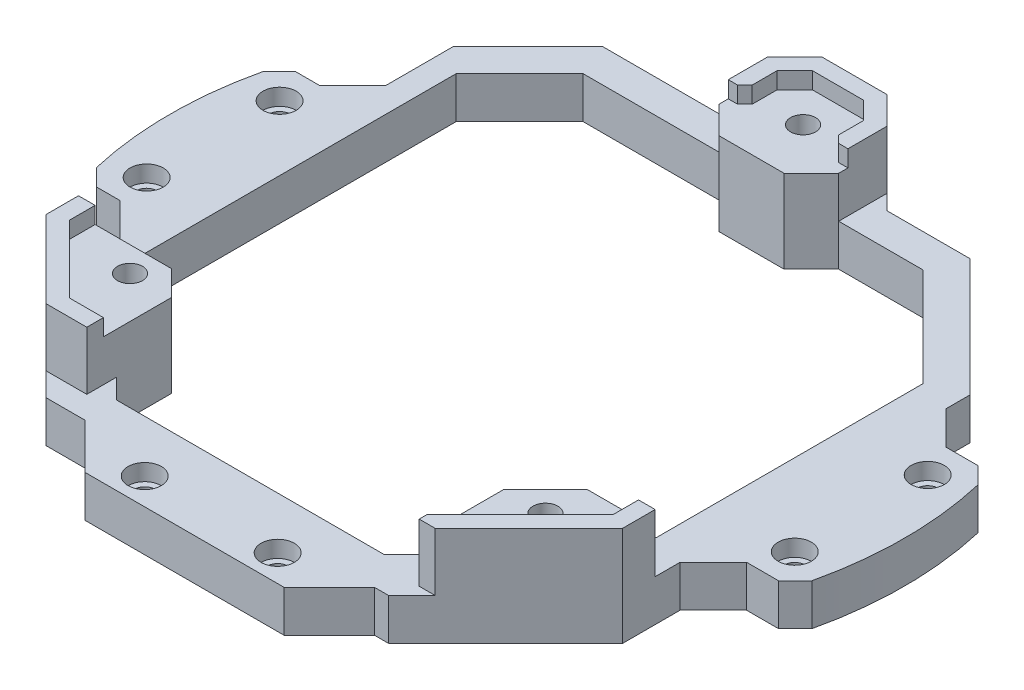
SolidWorks part; units mm, degrees
ref_plane "Спереди" through (0, 0, 0) normal (0, 0, 1) x (1, 0, 0)
ref_plane "Сверху" through (0, 0, 0) normal (0, 1, 0) x (1, 0, 0)
ref_plane "Справа" through (0, 0, 0) normal (1, 0, 0) x (0, 0, -1)
sketch "Эскиз2" plane through (0, 0, 0) normal (0, 1, 0) x (1, 0, 0)
  line L0 (3, 36) -> (-3, 36) construction
  line L1 (3, 36) -> (-3, 36) construction
  line L2 (0, 32) -> (5, 32) construction
  line L3 (5, 31) -> (5, 34) construction
  line L4 (-3.0828, 27.8) -> (-5.2, 29.9172)
  line L5 (5, 34) -> (3, 36) construction
  line L6 (-5, 34) -> (-5, 31) construction
  line L7 (-3, 36) -> (-5, 34) construction
  line L8 (5, 31) -> (5, 34) construction
  line L9 (5, 34) -> (3, 36) construction
  line L10 (-5, 34) -> (-5, 31) construction
  line L11 (-3, 36) -> (-5, 34) construction
  line L12 (5.2, 31) -> (5.2, 34.0828)
  line L13 (5.2, 34.0828) -> (3.0828, 36.2)
  line L14 (3.0828, 36.2) -> (-3.0828, 36.2)
  line L15 (-3.0828, 36.2) -> (-5.2, 34.0828)
  line L16 (-5.2, 34.0828) -> (-5.2, 31)
  line L17 (7.2, 31) -> (7.2, 34.9113)
  line L18 (7.2, 34.9113) -> (3.9113, 38.2)
  line L19 (3.9113, 38.2) -> (-3.9113, 38.2)
  line L20 (-3.9113, 38.2) -> (-7.2, 34.9113)
  line L21 (-7.2, 34.9113) -> (-7.2, 31)
  line L22 (-3.9113, 25.8) -> (-7.2, 29.0887)
  line L23 (5.2, 29.9172) -> (3.0828, 27.8)
  line L24 (3.0828, 27.8) -> (-3.0828, 27.8)
  line L25 (3.9113, 25.8) -> (-3.9113, 25.8)
  line L26 (7.2, 29.0887) -> (3.9113, 25.8)
  line L27 (-5.2, 31) -> (-5.2, 29.9172)
  line L28 (-7.2, 31) -> (-7.2, 29.0887)
  line L29 (5.2, 29.9172) -> (5.2, 31)
  line L30 (7.2, 29.0887) -> (7.2, 31)
  line L33 (20, -33) -> (20, -24)
  line L34 (20, -24) -> (25, -19)
  line L35 (25, -19) -> (31, -19)
  line L36 (31, -22) -> (31, 25) construction
  line L38 (18, -35) -> (31, -22) construction
  line L39 (20, -33) -> (31, -22) construction
  line L40 (21.9113, -34.2) -> (33.2, -22.9113)
  line L41 (20.1414, -33.1414) -> (31.2, -22.0828) construction
  line L43 (31.2, -22.0828) -> (31.2, -19) construction
  line L44 (20.1414, -33.1414) -> (31.1414, -22.1414) construction
  line L45 (33.2, -22.9113) -> (33.2, -19)
  line L46 (20, -33) -> (20.1414, -33.1414)
  line L47 (31, -19) -> (33.2, -19)
  line L48 (-20, -32) -> (-20, -24)
  line L49 (-24, -32) -> (-10, -32) construction
  line L50 (-20, -24) -> (-23, -21)
  line L51 (-23, -21) -> (-32, -21)
  line L52 (-32, 22) -> (-32, -24) construction
  line L53 (-32, -24) -> (-24, -32) construction
  line L54 (-32, -21) -> (-32, -24) construction
  line L55 (-24, -32) -> (-20, -32) construction
  line L56 (-32, -24) -> (-24, -32) construction
  line L57 (-32, 22) -> (-32, -21) construction
  line L58 (-20, -32) -> (-10, -32) construction
  line L59 (-34.2, -21) -> (-34.2, -24.9113)
  line L60 (-34.2, -24.9113) -> (-24.9113, -34.2)
  line L61 (-24.9113, -34.2) -> (-20, -34.2)
  line L62 (-34.2, -21) -> (-32, -21)
  line L63 (-20, -34.2) -> (-20, -32)
  line L64 (-1020, -34.2) -> (48980, -34.2) construction
  line L65 (20, -33) -> (20, -34.2)
  line L66 (20, -34.2) -> (21.9113, -34.2)
  line L68 (21.5556, -34.5556) -> (33.2, -22.9113) construction
  circle A0 centre (25, -24) radius 1.25 construction
  circle A1 centre (0, 32) radius 1.25 construction
  circle A2 centre (-25, -24) radius 1.25 construction
  circle A3 centre (25, -24) radius 1.25 construction
  circle A4 centre (0, 32) radius 1.25 construction
  circle A5 centre (-25, -24) radius 1.25 construction
  circle A6 centre (-25, -24) radius 1.5
  circle A7 centre (25, -24) radius 1.5
  circle A8 centre (0, 32) radius 1.5
  dimension "D1" = 3
  dimension "D4" = 5
  dimension "D5" = 5
  dimension "D7" = 0.2
  dimension "D9" = 5
  dimension "D10" = 3
  dimension "D2" = 0.2
  dimension "D3" = 2
  dimension "D6" = 0.2
  dimension "D8" = 2
  dimension "D11" = 2.2
extrude "Бобышка-Вытянуть2" add sketch "Эскиз2" against normal blind 5 contours L61 L63 L48 L50 L51 L62 L59 L60 A6 | L47 L35 L34 L33 L46 L40 L45 A7 | L26 L30 L17 L18 L19 L20 L21 L28 L22 L25 L29 L23 L24 L4 L27 L16 L15 L14 L13 L12 | L23 L29 L12 L13 L14 L15 L16 L27 L4 L24 A8
sketch "Эскиз3" plane through (0, 0, 0) normal (0, 1, 0) x (1, 0, 0)
  line L11 (-24, -32) -> (-10, -32) construction
  line L12 (7.2, 29.0887) -> (7.2, 34.9113) construction
  line L15 (7.2, 34.9113) -> (3.9113, 38.2) construction
  line L22 (-32, -24) -> (-24, -32) construction
  line L23 (-32, 22) -> (-32, -24) construction
  line L24 (3.9113, 38.2) -> (-3.9113, 38.2) construction
  line L25 (-7.2, 34.9113) -> (-7.2, 29.0887) construction
  line L34 (-3.9113, 38.2) -> (-7.2, 34.9113) construction
  line L35 (7.2, 30.2) -> (7.2, 34.9113)
  line L36 (7.2, 34.9113) -> (3.9113, 38.2)
  line L37 (3.9113, 38.2) -> (-3.9113, 38.2)
  line L38 (-7.2, 34.9113) -> (-7.2, 30.2)
  line L39 (-3.9113, 38.2) -> (-7.2, 34.9113)
  line L40 (26, 30) -> (6, 30) construction
  line L41 (-24, -32) -> (-20, -32) construction
  line L42 (-32, -24) -> (-24, -32) construction
  line L43 (-32, -21) -> (-32, -24) construction
  line L44 (-24.9113, -34.2) -> (-20, -34.2)
  line L45 (-20, -34.2) -> (-20, -24)
  line L46 (-20, -24) -> (-23, -21)
  line L47 (-23, -21) -> (-34.2, -21)
  line L55 (6, 30) -> (5, 31) construction
  line L56 (-34.2, -21) -> (-34.2, -24.9113)
  line L57 (5, 31) -> (5, 34) construction
  line L58 (-34.2, -24.9113) -> (-24.9113, -34.2)
  line L59 (-24.9113, -34.2) -> (-20, -34.2)
  line L60 (-20, -34.2) -> (-20, -32.2)
  line L61 (-20, -24) -> (-23, -21) construction
  line L62 (-32.2, -21) -> (-34.2, -21)
  line L65 (-34.2, -21) -> (-34.2, -24.9113)
  line L66 (-34.2, -24.9113) -> (-24.9113, -34.2)
  line L67 (-32, 22) -> (-32, -21) construction
  line L68 (-23, -21) -> (-32, -21) construction
  line L69 (-20, -32) -> (-20, -24) construction
  line L70 (-20, -32) -> (-10, -32) construction
  line L71 (-32.2, -21) -> (-32.2, -24.0828)
  line L72 (-32.2, -24.0828) -> (-24.0828, -32.2)
  line L73 (-24.0828, -32.2) -> (-20, -32.2)
  line L74 (-20, -32.2) -> (-20, -32) construction
  line L75 (5, 34) -> (3, 36) construction
  line L77 (-32, -21) -> (-32.2, -21) construction
  line L100 (3, 36) -> (-3, 36) construction
  line L101 (-3, 36) -> (-5, 34) construction
  line L102 (-5, 34) -> (-5, 31) construction
  line L103 (-5, 31) -> (-6, 30) construction
  line L104 (-6, 30) -> (-15, 30) construction
  line L105 (7.2, 30) -> (6, 30) construction
  line L106 (6, 30) -> (5, 31) construction
  line L107 (5, 31) -> (5, 34) construction
  line L108 (5, 34) -> (3, 36) construction
  line L109 (3, 36) -> (-3, 36) construction
  line L110 (-3, 36) -> (-5, 34) construction
  line L111 (-5, 34) -> (-5, 31) construction
  line L112 (-5, 31) -> (-6, 30) construction
  line L113 (-6, 30) -> (-7.2, 30) construction
  line L117 (7.2, 29.0887) -> (7.2, 30) construction
  line L118 (7.2, 30.2) -> (6.0828, 30.2)
  line L119 (6.0828, 30.2) -> (5.2, 31.0828)
  line L120 (5.2, 31.0828) -> (5.2, 34.0828)
  line L121 (5.2, 34.0828) -> (3.0828, 36.2)
  line L122 (3.0828, 36.2) -> (-3.0828, 36.2)
  line L123 (-3.0828, 36.2) -> (-5.2, 34.0828)
  line L124 (-5.2, 34.0828) -> (-5.2, 31.0828)
  line L125 (-5.2, 31.0828) -> (-6.0828, 30.2)
  line L126 (-6.0828, 30.2) -> (-7.2, 30.2)
  line L127 (-7.2, 30.2) -> (-7.2, 30) construction
  line L128 (7.2, 30) -> (7.2, 30.2) construction
  dimension "D1" = 0
  dimension "D2" = 0.2
  dimension "D5" = 0.2
extrude "Бобышка-Вытянуть5" add sketch "Эскиз3" along normal blind 2
sketch "Эскиз5" plane through (0, 0, 0) normal (0, 1, 0) x (1, 0, 0)
  line L0 (25, -19) -> (33.2, -19) construction
  line L1 (31, -22) -> (31, 25) construction
  line L2 (31.2, -19) -> (33.2, -19)
  line L10 (20, -24) -> (20, -34.2) construction
  line L11 (20, -34.2) -> (21.9113, -34.2) construction
  line L12 (21.9113, -34.2) -> (33.2, -22.9113) construction
  line L13 (33.2, -22.9113) -> (33.2, -19) construction
  line L14 (31, -22) -> (31, -19) construction
  line L15 (20, -33.2828) -> (20, -34.2)
  line L16 (20, -34.2) -> (21.9113, -34.2)
  line L17 (21.9113, -34.2) -> (33.2, -22.9113)
  line L18 (33.2, -22.9113) -> (33.2, -19)
  line L19 (20, -33.2828) -> (31.2, -22.0828)
  line L20 (18, -35) -> (31, -22) construction
  line L21 (20, -33) -> (31, -22) construction
  line L22 (31.2, -22.0828) -> (31.2, -19)
  line L23 (18.1414, -35.1414) -> (31.2, -22.0828) construction
  line L24 (18, -35) -> (31, -22) construction
  line L25 (20, -33) -> (20, -33.2828) construction
  line L26 (31, -19) -> (31.2, -19) construction
  dimension "D1" = 0.2
extrude "Бобышка-Вытянуть6" add sketch "Эскиз5" along normal up to surface (2 mm away) up to face at (-27.7243, 2, 27.9743)
sketch "Эскиз6" plane through (0, -5, 0) normal (0, -1, 0) x (1, 0, 0)
  line L0 (7.2, -29.0887) -> (3.9113, -25.8) construction
  line L1 (3.9113, -25.8) -> (-3.9113, -25.8) construction
  line L2 (-3.9113, -25.8) -> (-7.2, -29.0887) construction
  line L3 (-7.2, -29.0887) -> (-7.2, -34.9113) construction
  line L4 (-7.2, -34.9113) -> (-3.9113, -38.2) construction
  line L5 (-3.9113, -38.2) -> (3.9113, -38.2) construction
  line L6 (3.9113, -38.2) -> (7.2, -34.9113) construction
  line L7 (7.2, -34.9113) -> (7.2, -29.0887) construction
  line L8 (20, 34.2) -> (20, 24) construction
  line L9 (20, 24) -> (25, 19) construction
  line L10 (25, 19) -> (33.2, 19) construction
  line L11 (33.2, 19) -> (33.2, 22.9113) construction
  line L12 (33.2, 22.9113) -> (21.9113, 34.2) construction
  line L13 (21.9113, 34.2) -> (20, 34.2) construction
  line L14 (-20, 34.2) -> (-24.9113, 34.2) construction
  line L15 (-24.9113, 34.2) -> (-34.2, 24.9113) construction
  line L16 (-34.2, 24.9113) -> (-34.2, 21) construction
  line L17 (-34.2, 21) -> (-23, 21) construction
  line L18 (-23, 21) -> (-20, 24) construction
  line L19 (-20, 24) -> (-20, 34.2) construction
  line L20 (7.2, -29.0887) -> (3.9113, -25.8)
  line L21 (3.9113, -25.8) -> (-3.9113, -25.8)
  line L22 (-3.9113, -25.8) -> (-7.2, -29.0887)
  line L23 (-7.2, -33.0887) -> (-7.2, -34.9113) construction
  line L24 (-7.2, -34.9113) -> (-3.9113, -38.2)
  line L25 (-3.9113, -38.2) -> (3.9113, -38.2)
  line L26 (3.9113, -38.2) -> (7.2, -34.9113)
  line L27 (7.2, -34.9113) -> (7.2, -29.0887) construction
  line L28 (20, 27.626) -> (20, 24)
  line L29 (20, 24) -> (25, 19)
  line L30 (25, 19) -> (29.2, 19) construction
  line L31 (33.2, 19) -> (33.2, 22.9113)
  line L32 (33.2, 22.9113) -> (21.9113, 34.2)
  line L33 (21.9113, 34.2) -> (20, 34.2) construction
  line L34 (-20, 34.2) -> (-24.9113, 34.2) construction
  line L35 (-24.9113, 34.2) -> (-34.2, 24.9113)
  line L36 (-34.2, 24.9113) -> (-34.2, 21)
  line L37 (-29.626, 21) -> (-23, 21)
  line L38 (-23, 21) -> (-20, 24)
  line L39 (-20, 24) -> (-20, 30.626)
  line L40 (-8, 37) -> (13, 37) construction
  line L41 (-8, 37) -> (13, 37)
  line L42 (21.9113, 34.2) -> (19.1113, 37)
  line L43 (19.1113, 37) -> (13, 37)
  line L44 (-8, 37) -> (-22.1113, 37)
  line L45 (-22.1113, 37) -> (-24.9113, 34.2)
  line L46 (-20, 30.626) -> (-17.626, 33)
  line L47 (-17.626, 33) -> (14.626, 33)
  line L48 (14.626, 33) -> (20, 27.626)
  line L49 (-34.2, 21) -> (-34.2, -24.0887)
  line L50 (-34.2, -24.0887) -> (-25.2, -33.0887)
  line L51 (-31.2, 19.426) -> (-31.2, -21.4319)
  line L52 (-31.2, 21) -> (-29.626, 21) construction
  line L53 (-31.2, -21.4319) -> (-23.5431, -29.0887)
  line L54 (-23.5431, -29.0887) -> (-7.2, -29.0887)
  line L55 (-25.2, -33.0887) -> (-9.0225, -33.0887)
  line L56 (-7.2, -34.9113) -> (-9.0225, -33.0887)
  line L57 (-9.0225, -33.0887) -> (-7.2, -33.0887) construction
  line L58 (-7.2, -29.0887) -> (-7.2, -33.0887) construction
  line L59 (-34.2, 21) -> (-31.2, 21) construction
  line L60 (-20, 30.626) -> (-20, 34.2) construction
  line L61 (-31.2, 19.426) -> (-29.626, 21)
  line L62 (-31.2, 21) -> (-31.2, 19.426) construction
  line L63 (20, 34.2) -> (20, 27.626) construction
  line L64 (33.2, 19) -> (33.2, -18.9113)
  line L65 (33.2, -18.9113) -> (19.0225, -33.0887)
  line L66 (19.0225, -33.0887) -> (9.0225, -33.0887)
  line L67 (9.0225, -33.0887) -> (7.2, -34.9113)
  line L68 (7.2, -29.0887) -> (17.3657, -29.0887)
  line L69 (17.3657, -29.0887) -> (29.2, -17.2544)
  line L70 (29.2, -17.2544) -> (29.2, 14.8)
  line L71 (25, 19) -> (29.2, 14.8)
  line L72 (29.2, 19) -> (33.2, 19) construction
  line L73 (29.2, 14.8) -> (29.2, 19) construction
  circle A0 centre (0, 0) radius 44.5 construction
  dimension "D7" = 89
  dimension "D1" = 4
  dimension "D2" = 6
  dimension "D3" = 6
  dimension "D4" = 3
  dimension "D5" = 4
  dimension "D6" = 4
  dimension "D8" = 18
  dimension "D9" = 6
  dimension "D10" = 4
  dimension "D11" = 10
  dimension "D12" = 4
extrude "Бобышка-Вытянуть7" add sketch "Эскиз6" along normal blind 5
sketch "Эскиз11" plane through (0, -5, 0) normal (0, 1, 0) x (1, 0, 0)
  line L0 (-1000, 0) -> (49000, 0) construction
  line L1 (0, -1000) -> (0, 49000) construction
  line L2 (39, -1000) -> (39, 49000) construction
  line L3 (-1000, -39.23) -> (49000, -39.23) construction
  line L4 (41.0539, 12) -> (33.2, 12)
  line L5 (33.2, 18.9113) -> (33.2, -19) construction
  line L6 (41.0539, -12) -> (33.2, -12)
  line L7 (41.0539, 12) -> (43.0539, 10)
  line L8 (41.0539, -12) -> (43.0539, -10)
  line L9 (42.5399, -12) -> (41.0539, -12) construction
  line L10 (42.5399, 12) -> (41.0539, 12) construction
  line L11 (33.2, 12) -> (33.2, -12)
  line L12 (33.2, 18.9113) -> (33.2, 12) construction
  line L13 (33.2, -12) -> (33.2, -19) construction
  line L14 (-41.0539, 12) -> (-34.2, 12)
  line L15 (-41.0539, 12) -> (-43.0539, 10)
  line L16 (-41.0539, -12) -> (-43.0539, -10)
  line L17 (-33.2, 0) -> (-33.2, -12) construction
  line L18 (-41.0539, -12) -> (-34.2, -12)
  line L19 (-34.2, -21) -> (-34.2, 24.0887) construction
  line L20 (-34.2, -12) -> (-34.2, 12)
  line L21 (-34.2, 12) -> (-34.2, 24.0887) construction
  line L22 (-34.2, 12) -> (-33.2, 12) construction
  line L23 (-33.2, 12) -> (-33.2, 0) construction
  line L24 (-34.2, -12) -> (-33.2, -12) construction
  line L25 (-34.2, -21) -> (-34.2, -12) construction
  line L26 (-12, -42.44) -> (12, -42.44)
  line L27 (12, -42.44) -> (17.44, -37)
  line L28 (19.1113, -37) -> (-22.1113, -37) construction
  line L29 (-12, -42.44) -> (-17.44, -37)
  line L30 (17.44, -37) -> (-17.44, -37)
  line L31 (-17.44, -37) -> (-22.1113, -37) construction
  circle A0 centre (39, 8) radius 1.25
  circle A1 centre (39, -8) radius 1.25
  circle A2 centre (-39, 8) radius 1.25
  circle A3 centre (-39, -8) radius 1.25
  circle A4 centre (8, -39.23) radius 1.25
  circle A5 centre (-8, -39.23) radius 1.25
  arc A6 (43.0539, 10) -> (43.0539, -10) centre (0, 0) cw
  arc A7 (43.0539, -10) -> (42.5399, -12) centre (0, 0) cw construction
  arc A8 (42.5399, 12) -> (43.0539, 10) centre (0, 0) cw construction
  arc A9 (-43.0539, 10) -> (-43.0539, -10) centre (0, 0) ccw
  dimension "D3" = 2.5
  dimension "D6" = 44.2
  dimension "D1" = 39
  dimension "D2" = 16
  dimension "D4" = 39.23
  dimension "D5" = 16
  dimension "D7" = 24
  dimension "D8" = 45
  dimension "D9" = 20
  dimension "D10" = 42.44
  dimension "D11" = 24
  dimension "D12" = 45
extrude "Бобышка-Вытянуть8" add sketch "Эскиз11" against normal up to surface (5 mm away) up to face at (-0.9315, -10, -10.8277)
chamfer "Фаска1" distance 4 angle 45 4 edges at (33.2, -7.5, -12) (-34.2, -7.5, -12) (-34.2, -7.5, 12) (33.2, -7.5, 12)
sketch "Эскиз12" plane through (0, -5, 0) normal (0, 1, 0) x (1, 0, 0)
  circle A0 centre (-8, -39.23) radius 1.25 construction
  circle A1 centre (8, -39.23) radius 1.25 construction
  circle A2 centre (39, -8) radius 1.25 construction
  circle A3 centre (39, 8) radius 1.25 construction
  circle A4 centre (-39, -8) radius 1.25 construction
  circle A5 centre (-39, 8) radius 1.25 construction
  circle A6 centre (-8, -39.23) radius 1.25 construction
  circle A7 centre (8, -39.23) radius 1.25 construction
  circle A8 centre (39, -8) radius 1.25 construction
  circle A9 centre (39, 8) radius 1.25 construction
  circle A10 centre (-39, -8) radius 1.25 construction
  circle A11 centre (-39, 8) radius 1.25 construction
  circle A12 centre (-39, 8) radius 2
  circle A13 centre (-39, -8) radius 2
  circle A14 centre (39, 8) radius 2
  circle A15 centre (39, -8) radius 2
  circle A16 centre (8, -39.23) radius 2
  circle A17 centre (-8, -39.23) radius 2
  dimension "D1" = 4
extrude "Вырез-Вытянуть1" cut sketch "Эскиз12" against normal blind 2
